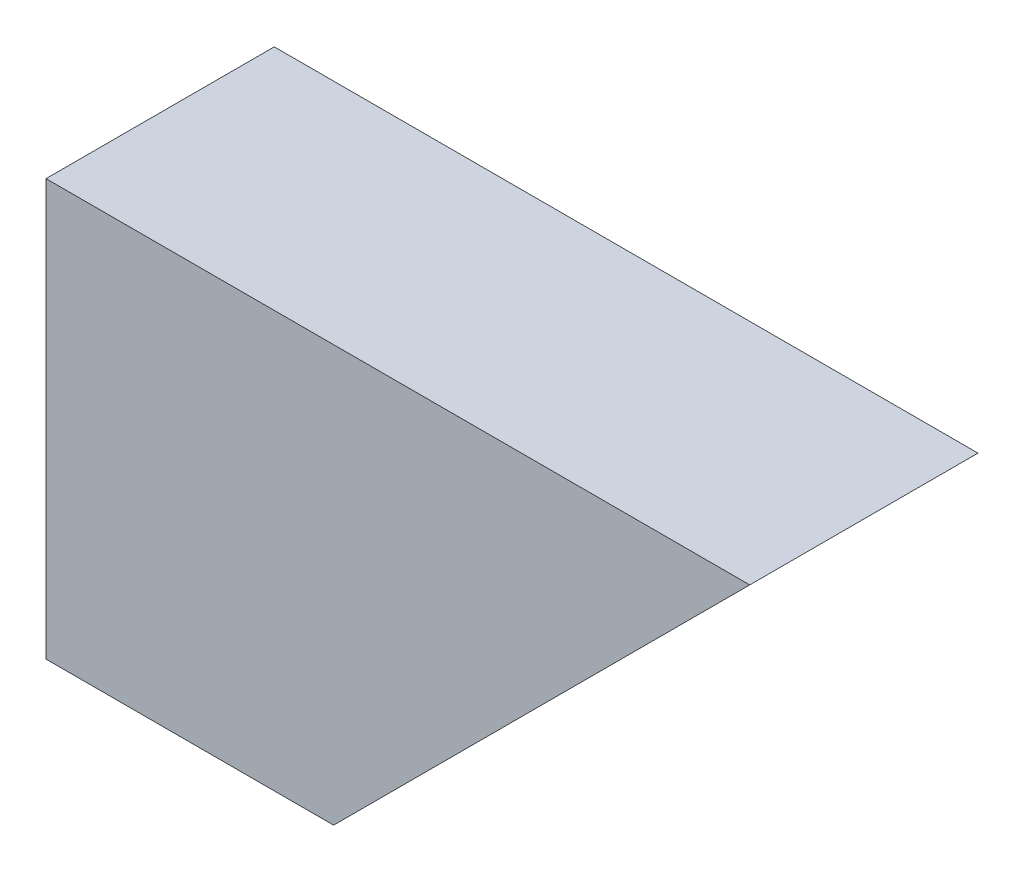
SolidWorks part; units mm, degrees
ref_plane "Plan de face" through (0, 0, 0) normal (0, 0, 1) x (1, 0, 0)
ref_plane "Plan de dessus" through (0, 0, 0) normal (0, 1, 0) x (1, 0, 0)
ref_plane "Plan de droite" through (0, 0, 0) normal (1, 0, 0) x (0, 0, -1)
sketch "Main-Sketch" plane through (0, 0, 0) normal (0, 0, 1) x (1, 0, 0)
  line L0 (0, 91.15) -> (154.15, 91.15)
  line L1 (154.15, 91.15) -> (63, 0)
  line L2 (63, 0) -> (0, 0)
  line L3 (0, 0) -> (0, 91.15)
  point P6 (7.2535, 108.6096)
  dimension "D1" = 63
  dimension "D2" = 154.15
  dimension "D3" = 135
extrude "Main-Extrusion" add sketch "Main-Sketch" along normal blind 50
